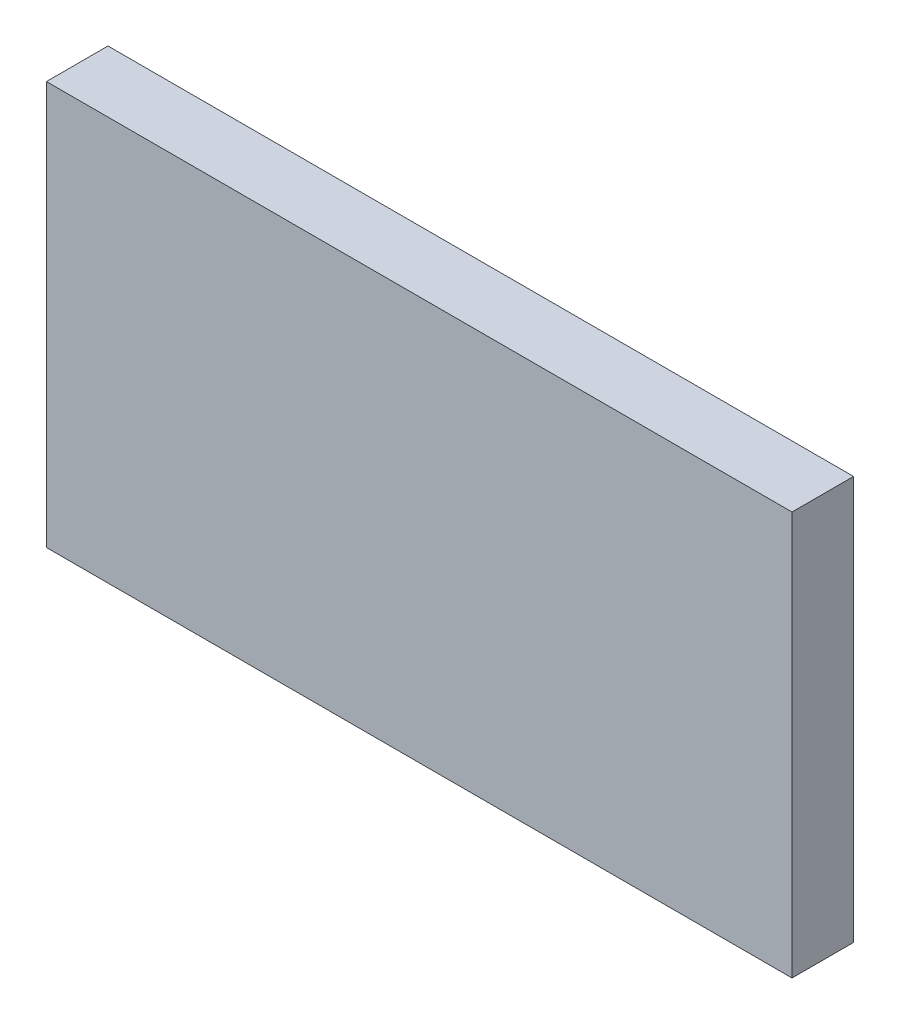
SolidWorks part; units mm, degrees
ref_plane "Plan de face" through (0, 0, 0) normal (0, 0, 1) x (1, 0, 0)
ref_plane "Plan de dessus" through (0, 0, 0) normal (0, 1, 0) x (1, 0, 0)
ref_plane "Plan de droite" through (0, 0, 0) normal (1, 0, 0) x (0, 0, -1)
sketch "Esquisse1" plane through (0, 0, 0) normal (0, 0, 1) x (1, 0, 0)
  line L0 (0, 0) -> (109, 0)
  line L1 (0, 0) -> (0, -59)
  line L2 (0, -59) -> (109, -59)
  line L3 (109, -59) -> (109, 0)
extrude "Boss.-Extru.1" add sketch "Esquisse1" along normal blind 9
sketch "Esquisse2" plane through (0, 0, 0) normal (0, 0, 1) x (1, 0, 0)
  line L20 (106, -56) -> (3, -56)
  line L21 (3, -3) -> (3, -56)
  line L22 (3, -3) -> (106, -3)
  line L23 (106, -3) -> (106, -56)
extrude "Enlèv. mat.-Extru.1" cut sketch "Esquisse2" along normal blind 8
sketch "Esquisse3" plane through (0, 0, 0) normal (0, 0, 1) x (1, 0, 0)
  line L0 (106, -3) -> (96, -3)
  line L1 (106, -3) -> (3, -3) construction
  line L2 (96, -3) -> (96, -13)
  line L3 (96, -13) -> (106, -13)
  line L4 (106, -56) -> (106, -3) construction
  line L5 (106, -13) -> (106, -3)
  line L6 (106, -56) -> (96, -56)
  line L7 (3, -56) -> (106, -56) construction
  line L8 (96, -56) -> (96, -46)
  line L9 (96, -46) -> (106, -46)
  line L10 (106, -56) -> (106, -3) construction
  line L11 (106, -46) -> (106, -56)
  line L12 (3, -56) -> (13, -56)
  line L13 (13, -56) -> (13, -46)
  line L14 (13, -46) -> (3, -46)
  line L15 (3, -3) -> (3, -56) construction
  line L16 (3, -46) -> (3, -56)
  line L17 (3, -3) -> (13, -3)
  line L18 (106, -3) -> (3, -3) construction
  line L19 (13, -3) -> (13, -13)
  line L20 (13, -13) -> (3, -13)
  line L21 (3, -13) -> (3, -3)
extrude "Boss.-Extru.2" add sketch "Esquisse3" along normal blind 9
sketch "Esquisse4" plane through (0, 0, 0) normal (0, 0, 1) x (1, 0, 0)
  line L0 (106, -13) -> (96, -13)
  line L1 (96, -13) -> (96, -3)
  line L2 (96, -3) -> (106, -3)
  line L3 (106, -3) -> (106, -13)
  line L4 (106, -46) -> (96, -46)
  line L5 (106, -46) -> (96, -46) construction
  line L6 (106, -46) -> (106, -13) construction
  line L7 (96, -46) -> (96, -56)
  line L8 (96, -56) -> (106, -56)
  line L9 (106, -56) -> (106, -46)
  line L10 (3, -46) -> (13, -46)
  line L11 (13, -46) -> (13, -56)
  line L12 (13, -56) -> (3, -56)
  line L13 (3, -56) -> (3, -46)
  line L14 (3, -13) -> (13, -13)
  line L15 (13, -13) -> (13, -3)
  line L16 (13, -3) -> (3, -3)
  line L17 (3, -3) -> (3, -13)
extrude "Enlèv. mat.-Extru.2" cut sketch "Esquisse4" along normal blind 2
